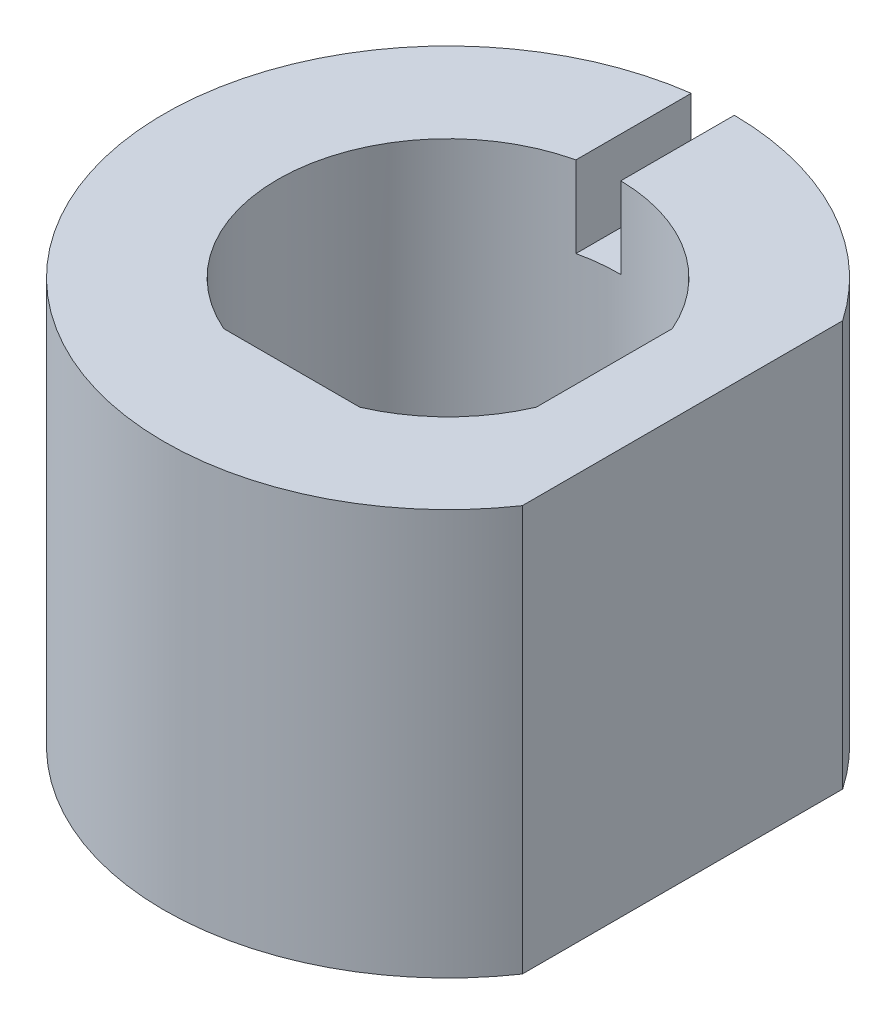
SolidWorks part; units mm, degrees
ref_plane "Спереди" through (0, 0, 0) normal (0, 0, 1) x (1, 0, 0)
ref_plane "Сверху" through (0, 0, 0) normal (0, 1, 0) x (1, 0, 0)
ref_plane "Справа" through (0, 0, 0) normal (1, 0, 0) x (0, 0, -1)
sketch "Эскиз1" plane through (0, 0, 0) normal (0, 1, 0) x (1, 0, 0)
  line L1 (3.85, -1.6785) -> (3.85, 1.6785)
  line L2 (1.6785, -3.85) -> (-1.6785, -3.85)
  circle A0 centre (0, 0) radius 4.2 construction
  circle A1 centre (0, 0) radius 7
  arc A2 (1.6785, -3.85) -> (3.85, -1.6785) centre (0, 0) ccw
  arc A3 (3.85, 1.6785) -> (-1.6785, -3.85) centre (0, 0) ccw
  dimension "D1" = 14
  dimension "D2" = 8.4
  dimension "D3" = 3.85
extrude "Вытянуть1" add sketch "Эскиз1" along normal blind 10
sketch "Эскиз2" plane through (0, 0, 0) normal (0, 1, 0) x (1, 0, 0)
  line L0 (15.9, 1.5588) -> (15.9, -1.5588)
  line L1 (10.4412, -3.9) -> (13.5588, -3.9)
  circle A0 centre (12, 0) radius 7
  circle A1 centre (12, 0) radius 4.2 construction
  arc A2 (15.9, 1.5588) -> (10.4412, -3.9) centre (12, 0) ccw
  arc A3 (13.5588, -3.9) -> (15.9, -1.5588) centre (12, 0) ccw
  dimension "D1" = 8.4
  dimension "D2" = 14
  dimension "D3" = 12
  dimension "D4" = 3.9
extrude "Вытянуть2" add sketch "Эскиз2" along normal blind 5
sketch "Эскиз3" plane through (0, 0, 0) normal (0, 1, 0) x (1, 0, 0)
  line L0 (27.8, 1.8468) -> (27.8, -1.8468)
  line L1 (25.8468, -3.8) -> (22.1532, -3.8)
  circle A0 centre (24, 0) radius 4.225 construction
  circle A1 centre (24, 0) radius 7
  arc A2 (27.8, 1.8468) -> (22.1532, -3.8) centre (24, 0) ccw
  arc A3 (27.8, -1.8468) -> (25.8468, -3.8) centre (24, 0) cw
  dimension "D1" = 8.45
  dimension "D2" = 14
  dimension "D3" = 24
  dimension "D4" = 3.8
extrude "Вытянуть3" add sketch "Эскиз3" along normal blind 5
sketch "Эскиз4" plane through (0, 10, 0) normal (0, 1, 0) x (1, 0, 0)
  line L1 (-0.941, 9.0252) -> (0.059, 9.0252)
  line L2 (-0.941, 9.0252) -> (-0.941, 2.2921)
  line L3 (-0.941, 2.2921) -> (0.059, 2.2921)
  line L4 (0.059, 9.0252) -> (0.059, 2.2921)
  line L5 (10.7584, 9.0252) -> (11.7584, 9.0252)
  line L6 (10.7584, 9.0252) -> (10.7584, 1.6713)
  line L7 (10.7584, 1.6713) -> (11.7584, 1.6713)
  line L8 (11.7584, 9.0252) -> (11.7584, 1.6713)
  line L9 (12.9073, 9.0252) -> (13.9073, 9.0252)
  line L10 (12.9073, 9.0252) -> (12.9073, 1.6713)
  line L11 (12.9073, 1.6713) -> (13.9073, 1.6713)
  line L12 (13.9073, 9.0252) -> (13.9073, 1.6713)
  dimension "D1" = 1
extrude "Вытянуть7" cut sketch "Эскиз4" against normal blind 2
sketch "Эскиз5" plane through (0, 10, 0) normal (0, 1, 0) x (1, 0, 0)
  line L1 (5.78, 12.0814) -> (33.5364, 12.0814)
  line L2 (5.78, 12.0814) -> (5.78, -10.3146)
  line L3 (5.78, -10.3146) -> (33.5364, -10.3146)
  line L4 (33.5364, 12.0814) -> (33.5364, -10.3146)
extrude "Вытянуть8" cut sketch "Эскиз5" against normal blind 10
